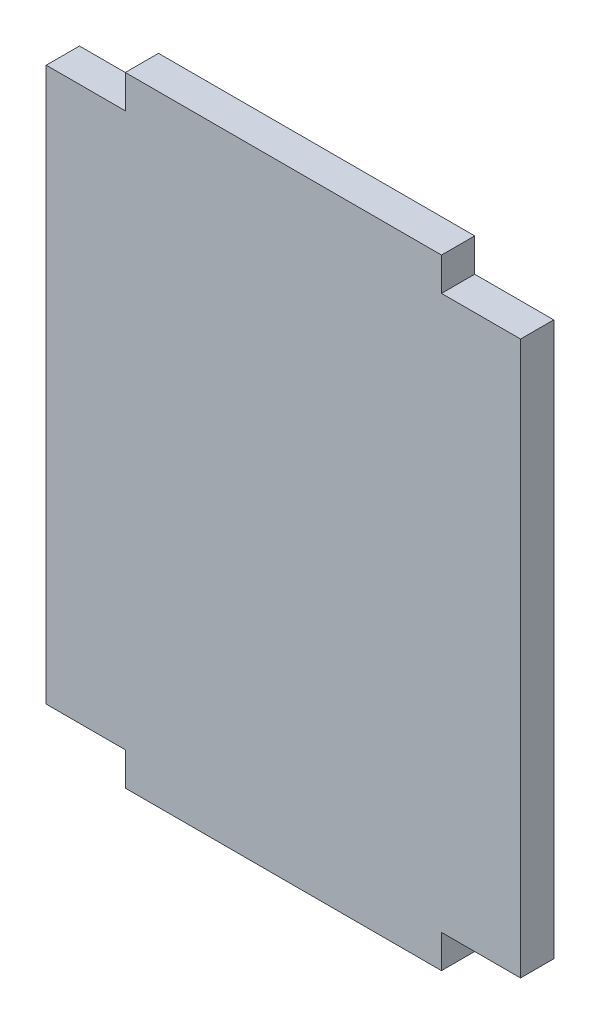
SolidWorks part; units mm, degrees
material "Pine"
ref_plane "Front Plane" through (0, 0, 0) normal (0, 0, 1) x (1, 0, 0)
ref_plane "Top Plane" through (0, 0, 0) normal (0, 1, 0) x (1, 0, 0)
ref_plane "Right Plane" through (0, 0, 0) normal (1, 0, 0) x (0, 0, -1)
sketch "Sketch1" plane through (0, 0, 0) normal (0, 0, 1) x (1, 0, 0)
  line L0 (0, 0) -> (50.8, 0)
  line L1 (50.8, 0) -> (50.8, -5.334)
  line L2 (50.8, -5.334) -> (63.5, -5.334)
  line L3 (63.5, -5.334) -> (63.5, -94.234)
  line L4 (63.5, -94.234) -> (50.8, -94.234)
  line L5 (50.8, -94.234) -> (50.8, -99.568)
  line L6 (50.8, -99.568) -> (0, -99.568)
  line L7 (0, -99.568) -> (0, -94.234)
  line L8 (0, -94.234) -> (-12.7, -94.234)
  line L9 (-12.7, -94.234) -> (-12.7, -5.334)
  line L10 (-12.7, -5.334) -> (0, -5.334)
  line L11 (0, -5.334) -> (0, 0)
  point P10 (0, 0)
  point P14 (0, -84.9806)
  dimension "D1" = 50.8
  dimension "D2" = 88.9
  dimension "D3" = 5.334
  dimension "D4" = 76.2
extrude "Boss-Extrude1" add sketch "Sketch1" along normal blind 5.334
